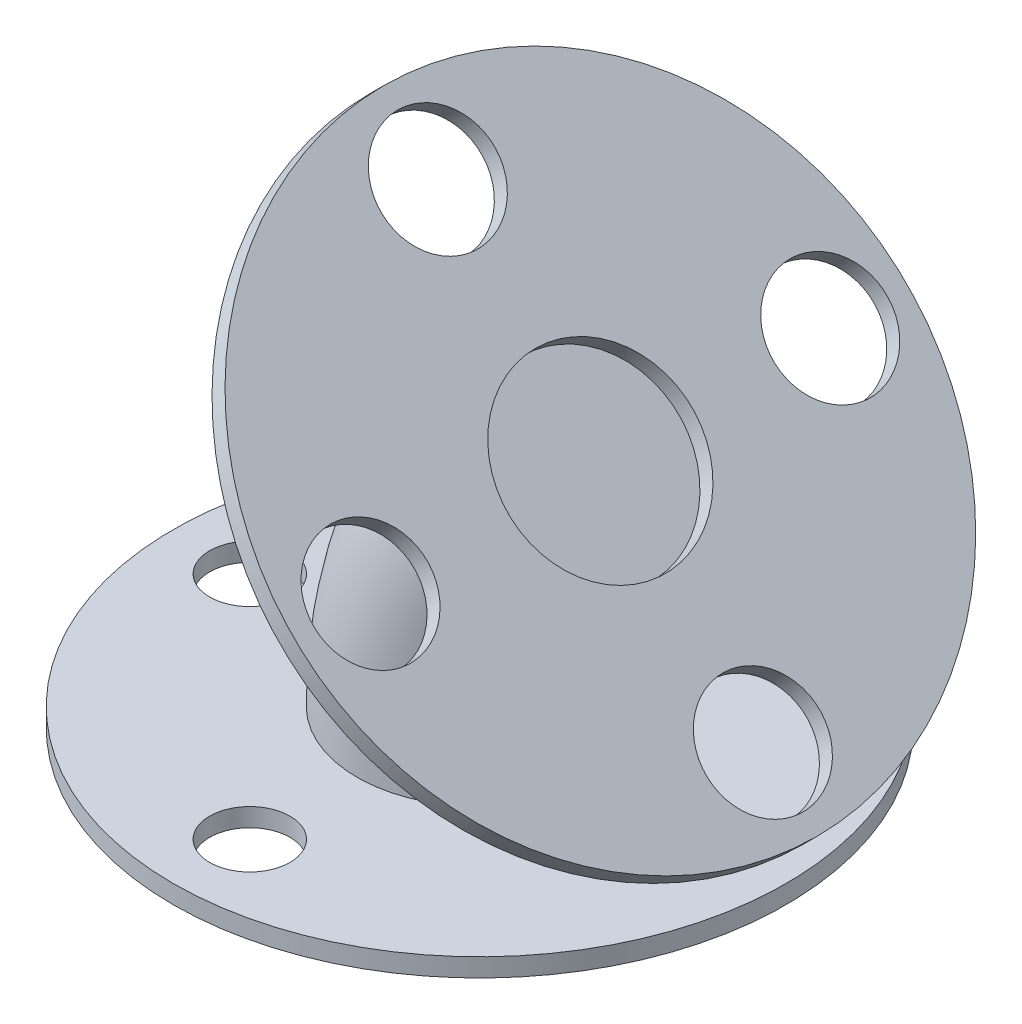
SolidWorks part; units mm, degrees
ref_plane "前视基准面" through (0, 0, 0) normal (0, 0, 1) x (1, 0, 0)
ref_plane "上视基准面" through (0, 0, 0) normal (0, 1, 0) x (1, 0, 0)
ref_plane "右视基准面" through (0, 0, 0) normal (1, 0, 0) x (0, 0, -1)
other "Configuration Table"
sketch "草图1" plane through (0, 0, 0) normal (0, 0, 1) x (1, 0, 0)
  line L0 (-60, 0) -> (60, 0) construction
  line L1 (0, 0) -> (-42.4264, 42.4264) construction
  arc A0 (-42.4264, 42.4264) -> (-60, 0) centre (0, 0) ccw
  dimension "D1" = 120
  dimension "D2" = 45
sketch "草图2" plane through (0, 0, 0) normal (0, 1, 0) x (1, 0, 0)
  line L0 (-60, 0) -> (60, 0) construction
  circle A0 centre (-60, 0) radius 20
  point P4 (0, 0)
  dimension "D1" = 40
sweep "扫描1" add profiles "草图2" path "草图1"
sketch "草图5" plane through (0, 0, 0) normal (0.7071, 0.7071, 0) x (0, 0, -1)
  line L0 (0, 0) -> (0, 60) construction
  circle A0 centre (0, 60) radius 50
  dimension "D1" = 100
extrude "凸台-拉伸1" add sketch "草图5" along normal blind 3
sketch "草图6" plane through (2.1213, 2.1213, 0) normal (0.7071, 0.7071, 0) x (0, 0, -1)
  circle A0 centre (0, 60) radius 15
  circle A1 centre (0, 60) radius 50 construction
  circle A2 centre (0, 60) radius 37.5 construction
  circle A3 centre (0, 97.5) radius 9.2614
  circle A4 centre (37.5, 60) radius 9.2614
  circle A5 centre (0, 22.5) radius 9.2614
  circle A6 centre (-37.5, 60) radius 9.2614
  point P16 (0, 60)
  dimension "D1" = 30
  dimension "D2" = 75
  dimension "D3" = 18.5227
  dimension "D4" = 4
extrude "切除-拉伸1" cut sketch "草图6" against normal blind 3
sketch "草图8" plane through (0, 0, 0) normal (0, -1, 0) x (1, 0, 0)
  circle A0 centre (-60, 0) radius 50
  dimension "D1" = 100
extrude "凸台-拉伸2" add sketch "草图8" along normal blind 3
sketch "草图9" plane through (0, -3, 0) normal (0, -1, 0) x (1, 0, 0)
  circle A0 centre (-60, 0) radius 15
  circle A1 centre (-60, 0) radius 50 construction
  circle A2 centre (-60, 0) radius 37.5 construction
  circle A3 centre (-60, 37.5) radius 6.5471
  circle A4 centre (-22.5, 0) radius 6.5471
  circle A5 centre (-60, -37.5) radius 6.5471
  circle A6 centre (-97.5, 0) radius 6.5471
  point P16 (-60, 0)
  dimension "D1" = 30
  dimension "D2" = 75
  dimension "D3" = 13.0943
  dimension "D4" = 4
extrude "切除-拉伸2" cut sketch "草图9" against normal blind 3
